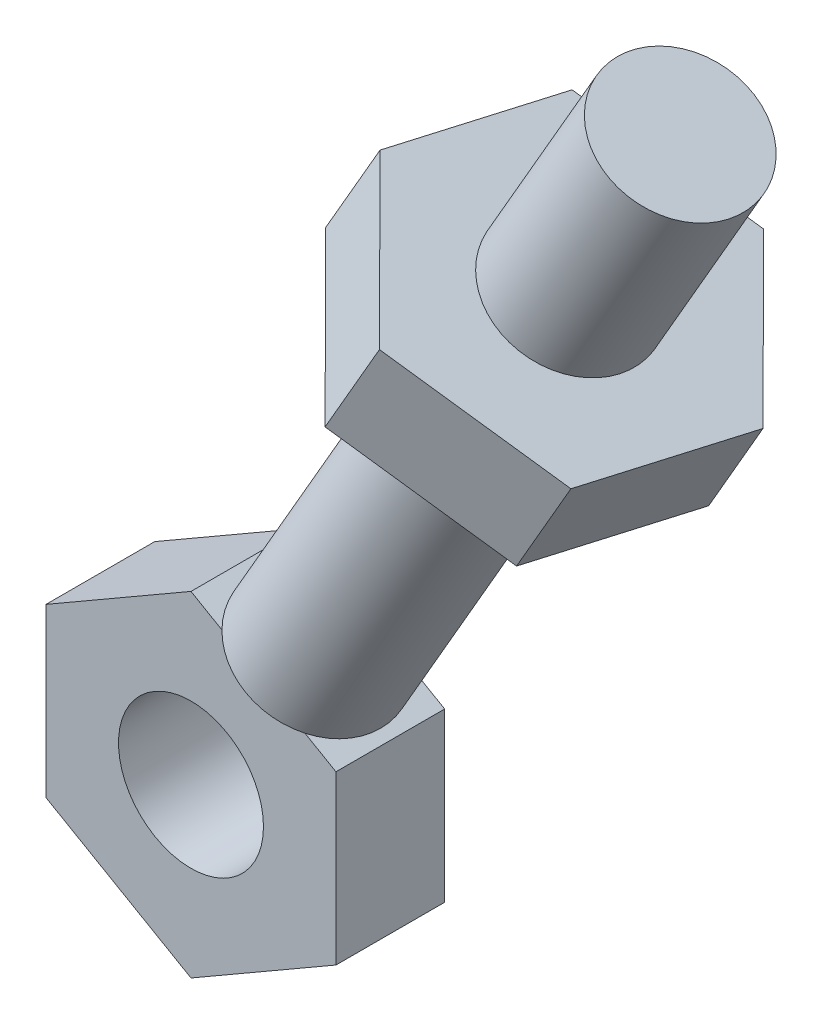
SolidWorks part; units mm, degrees
ref_plane "Front Plane" through (0, 0, 0) normal (0, 0, 1) x (1, 0, 0)
ref_plane "Top Plane" through (0, 0, 0) normal (0, 1, 0) x (1, 0, 0)
ref_plane "Right Plane" through (0, 0, 0) normal (1, 0, 0) x (0, 0, -1)
sketch "Sketch2" plane through (0, 0, 0) normal (0, 0, 1) x (1, 0, 0)
  line L1 (0, 4.6188) -> (-4, 2.3094)
  line L2 (-4, 2.3094) -> (-4, -2.3094)
  line L3 (-4, -2.3094) -> (0, -4.6188)
  line L4 (0, -4.6188) -> (4, -2.3094)
  line L5 (4, -2.3094) -> (4, 2.3094)
  line L6 (4, 2.3094) -> (0, 4.6188)
  circle A0 centre (0, 0) radius 4 construction
  circle A1 centre (0, 0) radius 2
  dimension "D1" = 8
extrude "Boss-Extrude2" add sketch "Sketch2" along normal blind 3
sketch "Sketch3" plane through (2, 3.4641, 0) normal (0.5, 0.866, 0) x (0.866, -0.5, 0)
  circle A0 centre (0, -1.5) radius 2
extrude "Boss-Extrude3" add sketch "Sketch3" along normal blind 20
ref_plane "Plane1" through (7.5, 12.9904, 0) normal (0.5, 0.866, 0) x (0.866, -0.5, 0)
sketch "Sketch4" plane through (7.5, 12.9904, 0) normal (0.5, 0.866, 0) x (0.866, -0.5, 0)
  line L1 (0.8853, 3.0332) -> (-3.4832, 1.5333)
  line L2 (-3.4832, 1.5333) -> (-4.3685, -2.9999)
  line L3 (-4.3685, -2.9999) -> (-0.8853, -6.0332)
  line L4 (-0.8853, -6.0332) -> (3.4832, -4.5333)
  line L5 (3.4832, -4.5333) -> (4.3685, -0.0001)
  line L6 (4.3685, -0.0001) -> (0.8853, 3.0332)
  circle A0 centre (0, -1.5) radius 4 construction
  dimension "D1" = 8
extrude "Boss-Extrude4" add sketch "Sketch4" along normal blind 3
